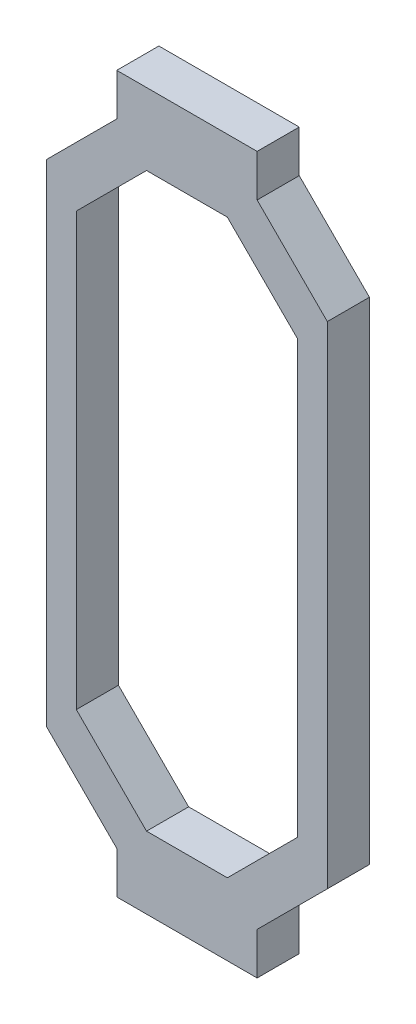
SolidWorks part; units mm, degrees
ref_plane "Front Plane" through (0, 0, 0) normal (0, 0, 1) x (1, 0, 0)
ref_plane "Top Plane" through (0, 0, 0) normal (0, 1, 0) x (1, 0, 0)
ref_plane "Right Plane" through (0, 0, 0) normal (1, 0, 0) x (0, 0, -1)
sketch "Sketch1" plane through (0, 0, 0) normal (0, 0, 1) x (1, 0, 0)
  line L16 (20, -35) -> (20, 35)
  line L17 (-20, 35) -> (-20, -35)
  line L18 (5.7574, 40.7574) -> (15.7574, 30.7574)
  line L19 (10, 45) -> (10, 51)
  line L20 (-10, 45) -> (-10, 51)
  line L21 (10, 51) -> (-10, 51)
  line L22 (-1.469, 0) -> (20, 0) construction
  line L23 (10, -45) -> (10, -51)
  line L24 (10, -51) -> (-10, -51)
  line L25 (-10, -45) -> (-10, -51)
  line L26 (-20, 35) -> (-10, 45)
  line L27 (10, 45) -> (20, 35)
  line L28 (10, -45) -> (20, -35)
  line L29 (-20, -35) -> (-10, -45)
  line L30 (-15.7574, 30.7574) -> (-5.7574, 40.7574)
  line L31 (5.7574, -40.7574) -> (15.7574, -30.7574)
  line L32 (-15.7574, -30.7574) -> (-5.7574, -40.7574)
  line L33 (-5.7574, -40.7574) -> (5.7574, -40.7574)
  line L34 (15.7574, -30.7574) -> (15.7574, 30.7574)
  line L35 (5.7574, 40.7574) -> (-5.7574, 40.7574)
  line L36 (-15.7574, 30.7574) -> (-15.7574, -30.7574)
  point P0 (-20, -45)
  point P2 (20, -45)
  point P3 (0, 0)
  point P4 (-20, 45)
  point P8 (20, 45)
  dimension "D2" = 6
  dimension "D5" = 6
  dimension "D3" = 6
  dimension "D4" = 6
extrude "Boss-Extrude1" add sketch "Sketch1" along normal blind 6
